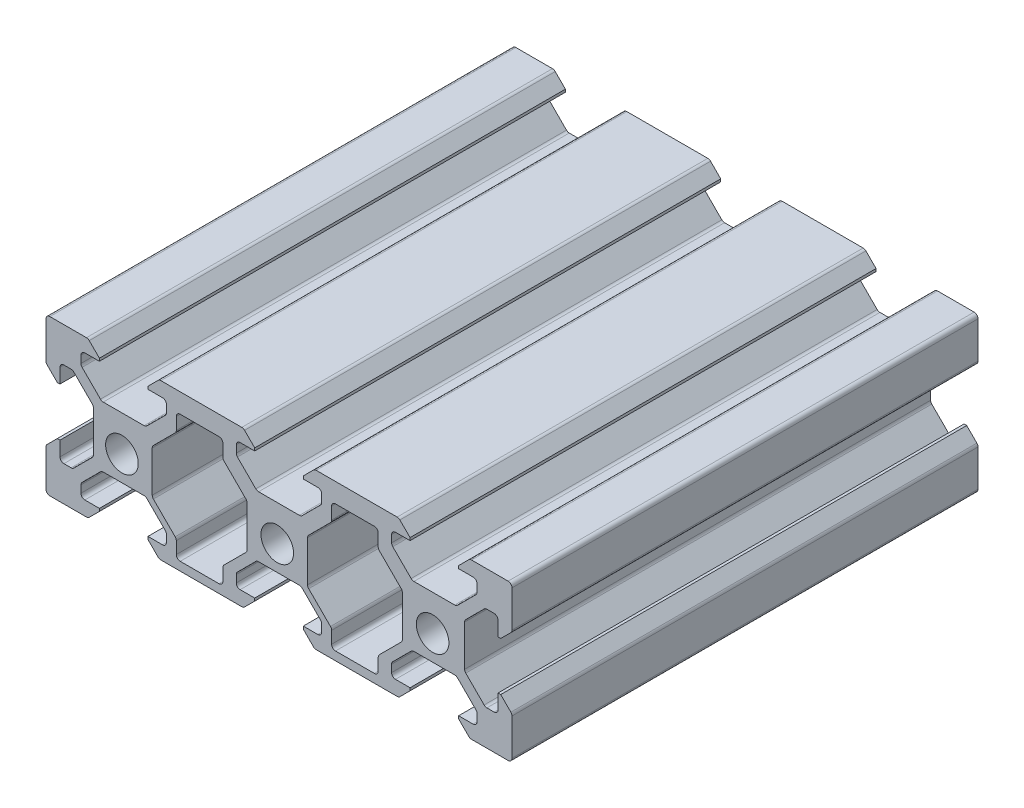
SolidWorks part; units mm, degrees
ref_plane "Front Plane" through (0, 0, 0) normal (0, 0, 1) x (1, 0, 0)
ref_plane "Top Plane" through (0, 0, 0) normal (0, 1, 0) x (1, 0, 0)
ref_plane "Right Plane" through (0, 0, 0) normal (1, 0, 0) x (0, 0, -1)
sketch "Sketch1" plane through (0, 0, 0) normal (0, 0, 1) x (1, 0, 0)
  line L24 (-13, 7.7) -> (-13, 6.1464)
  line L25 (-12.5, 8.2) -> (-7.5, 8.2)
  line L26 (-7, 6.1464) -> (-7, 7.7)
  line L27 (-6.8536, 5.7929) -> (-4.0464, 2.9858)
  line L28 (-3.9, 2.6322) -> (-3.9, -2.6322)
  line L29 (-15.9536, 2.9858) -> (-13.1464, 5.7929)
  line L30 (-16.1, -2.6322) -> (-16.1, 2.6322)
  line L31 (-13.1464, -5.7929) -> (-15.9536, -2.9858)
  line L32 (-13, -6.1464) -> (-13, -7.7)
  line L33 (-7.5, -8.2) -> (-12.5, -8.2)
  line L34 (-7, -7.7) -> (-7, -6.1464)
  line L35 (-4.0464, -2.9858) -> (-6.8536, -5.7929)
  line L36 (12.5, -8.2) -> (7.5, -8.2)
  line L37 (7, -6.1464) -> (7, -7.7)
  line L38 (6.8536, -5.7929) -> (4.0464, -2.9858)
  line L39 (3.9, -2.6322) -> (3.9, 2.6322)
  line L40 (4.0464, 2.9858) -> (6.8536, 5.7929)
  line L41 (7, 7.7) -> (7, 6.1464)
  line L42 (7.5, 8.2) -> (12.5, 8.2)
  line L43 (13, 6.1464) -> (13, 7.7)
  line L44 (13.1464, 5.7929) -> (15.9536, 2.9858)
  line L45 (16.1, 2.6322) -> (16.1, -2.6322)
  line L46 (15.9536, -2.9858) -> (13.1464, -5.7929)
  line L47 (13, -7.7) -> (13, -6.1464)
  line L200 (-22.4092, -3.2009) -> (-17.1447, -3.2009)
  line L201 (-16.7912, -3.3473) -> (-14.4234, -5.7151)
  line L202 (-14.277, -6.0686) -> (-14.277, -7.0009)
  line L203 (-14.777, -7.5009) -> (-16.652, -7.5009)
  line L204 (-16.652, -7.5009) -> (-16.652, -7.8459)
  line L205 (-16.652, -7.8459) -> (-15.3434, -9.1544)
  line L206 (-14.9898, -9.3009) -> (-4.5641, -9.3009)
  line L207 (-4.2105, -9.1544) -> (-2.902, -7.8459)
  line L208 (-2.902, -7.8459) -> (-2.902, -7.5009)
  line L209 (-2.902, -7.5009) -> (-4.777, -7.5009)
  line L210 (-5.277, -7.0009) -> (-5.277, -6.0686)
  line L211 (-5.1305, -5.7151) -> (-2.7627, -3.3473)
  line L212 (-2.4092, -3.2009) -> (2.8553, -3.2009)
  line L213 (3.2088, -3.3473) -> (5.5766, -5.7151)
  line L214 (5.723, -6.0686) -> (5.723, -7.0009)
  line L215 (5.223, -7.5009) -> (3.348, -7.5009)
  line L216 (3.348, -7.5009) -> (3.348, -7.8459)
  line L217 (3.348, -7.8459) -> (4.6566, -9.1544)
  line L218 (5.0102, -9.3009) -> (15.4359, -9.3009)
  line L219 (15.7895, -9.1544) -> (17.098, -7.8459)
  line L220 (17.098, -7.8459) -> (17.098, -7.5009)
  line L221 (17.098, -7.5009) -> (15.223, -7.5009)
  line L222 (14.723, -7.0009) -> (14.723, -6.0686)
  line L223 (14.8695, -5.7151) -> (17.2373, -3.3473)
  line L224 (17.5908, -3.2009) -> (22.8553, -3.2009)
  line L225 (23.2088, -3.3473) -> (25.5766, -5.7151)
  line L226 (25.723, -6.0686) -> (25.723, -7.0009)
  line L227 (25.223, -7.5009) -> (23.348, -7.5009)
  line L228 (23.348, -7.5009) -> (23.348, -7.8459)
  line L229 (23.348, -7.8459) -> (24.6566, -9.1544)
  line L230 (25.0102, -9.3009) -> (29.723, -9.3009)
  line L231 (30.223, -8.8009) -> (30.223, -4.088)
  line L232 (30.0766, -3.7344) -> (28.768, -2.4259)
  line L233 (28.768, -2.4259) -> (28.423, -2.4259)
  line L234 (28.423, -2.4259) -> (28.423, -4.3009)
  line L235 (27.923, -4.8009) -> (26.9908, -4.8009)
  line L236 (26.6373, -4.6544) -> (24.2695, -2.2866)
  line L237 (24.123, -1.9331) -> (24.123, 3.3314)
  line L238 (24.2695, 3.6849) -> (26.6373, 6.0527)
  line L239 (26.9908, 6.1991) -> (27.923, 6.1991)
  line L240 (28.423, 5.6991) -> (28.423, 3.8241)
  line L241 (28.423, 3.8241) -> (28.768, 3.8241)
  line L242 (28.768, 3.8241) -> (30.0766, 5.1327)
  line L243 (30.223, 5.4863) -> (30.223, 10.1991)
  line L244 (29.723, 10.6991) -> (25.0102, 10.6991)
  line L245 (24.6566, 10.5527) -> (23.348, 9.2441)
  line L246 (23.348, 9.2441) -> (23.348, 8.8991)
  line L247 (23.348, 8.8991) -> (25.223, 8.8991)
  line L248 (25.723, 8.3991) -> (25.723, 7.4669)
  line L249 (25.5766, 7.1134) -> (23.2088, 4.7456)
  line L250 (22.8553, 4.5991) -> (17.5908, 4.5991)
  line L251 (17.2373, 4.7456) -> (14.8695, 7.1134)
  line L252 (14.723, 7.4669) -> (14.723, 8.3991)
  line L253 (15.223, 8.8991) -> (17.098, 8.8991)
  line L254 (17.098, 8.8991) -> (17.098, 9.2441)
  line L255 (17.098, 9.2441) -> (15.7895, 10.5527)
  line L256 (15.4359, 10.6991) -> (5.0102, 10.6991)
  line L257 (4.6566, 10.5527) -> (3.348, 9.2441)
  line L258 (3.348, 9.2441) -> (3.348, 8.8991)
  line L259 (3.348, 8.8991) -> (5.223, 8.8991)
  line L260 (5.723, 8.3991) -> (5.723, 7.4669)
  line L261 (5.5766, 7.1134) -> (3.2088, 4.7456)
  line L262 (2.8553, 4.5991) -> (-2.4092, 4.5991)
  line L263 (-2.7627, 4.7456) -> (-5.1305, 7.1134)
  line L264 (-5.277, 7.4669) -> (-5.277, 8.3991)
  line L265 (-4.777, 8.8991) -> (-2.902, 8.8991)
  line L266 (-2.902, 8.8991) -> (-2.902, 9.2441)
  line L267 (-2.902, 9.2441) -> (-4.2105, 10.5527)
  line L268 (-4.5641, 10.6991) -> (-14.9898, 10.6991)
  line L269 (-15.3434, 10.5527) -> (-16.652, 9.2441)
  line L270 (-16.652, 9.2441) -> (-16.652, 8.8991)
  line L271 (-16.652, 8.8991) -> (-14.777, 8.8991)
  line L272 (-14.277, 8.3991) -> (-14.277, 7.4669)
  line L273 (-14.4234, 7.1134) -> (-16.7912, 4.7456)
  line L274 (-17.1447, 4.5991) -> (-22.4092, 4.5991)
  line L275 (-22.7627, 4.7456) -> (-25.1305, 7.1134)
  line L276 (-25.277, 7.4669) -> (-25.277, 8.3991)
  line L277 (-24.777, 8.8991) -> (-22.902, 8.8991)
  line L278 (-22.902, 8.8991) -> (-22.902, 9.2441)
  line L279 (-22.902, 9.2441) -> (-24.2105, 10.5527)
  line L280 (-24.5641, 10.6991) -> (-29.277, 10.6991)
  line L281 (-29.777, 10.1991) -> (-29.777, 5.4863)
  line L282 (-29.6305, 5.1327) -> (-28.322, 3.8241)
  line L283 (-28.322, 3.8241) -> (-27.977, 3.8241)
  line L284 (-27.977, 3.8241) -> (-27.977, 5.6991)
  line L285 (-27.477, 6.1991) -> (-26.5447, 6.1991)
  line L286 (-26.1912, 6.0527) -> (-23.8234, 3.6849)
  line L287 (-23.677, 3.3314) -> (-23.677, -1.9331)
  line L288 (-23.8234, -2.2866) -> (-26.1912, -4.6544)
  line L289 (-26.5447, -4.8009) -> (-27.477, -4.8009)
  line L290 (-27.977, -4.3009) -> (-27.977, -2.4259)
  line L291 (-27.977, -2.4259) -> (-28.322, -2.4259)
  line L292 (-28.322, -2.4259) -> (-29.6305, -3.7344)
  line L293 (-29.777, -4.088) -> (-29.777, -8.8009)
  line L294 (-29.277, -9.3009) -> (-24.5641, -9.3009)
  line L295 (-24.2105, -9.1544) -> (-22.902, -7.8459)
  line L296 (-22.902, -7.8459) -> (-22.902, -7.5009)
  line L297 (-22.902, -7.5009) -> (-24.777, -7.5009)
  line L298 (-25.277, -7.0009) -> (-25.277, -6.0686)
  line L299 (-25.1305, -5.7151) -> (-22.7627, -3.3473)
  arc A27 (-13.1464, 5.7929) -> (-13, 6.1464) centre (-13.5, 6.1464) ccw
  arc A28 (-12.5, 8.2) -> (-13, 7.7) centre (-12.5, 7.7) ccw
  arc A29 (-7, 7.7) -> (-7.5, 8.2) centre (-7.5, 7.7) ccw
  arc A30 (-7, 6.1464) -> (-6.8536, 5.7929) centre (-6.5, 6.1464) ccw
  arc A31 (-3.9, 2.6322) -> (-4.0464, 2.9858) centre (-4.4, 2.6322) ccw
  arc A32 (-15.9536, 2.9858) -> (-16.1, 2.6322) centre (-15.6, 2.6322) ccw
  circle A33 centre (-20, 0) radius 2.1
  arc A34 (-16.1, -2.6322) -> (-15.9536, -2.9858) centre (-15.6, -2.6322) ccw
  arc A35 (-13, -6.1464) -> (-13.1464, -5.7929) centre (-13.5, -6.1464) ccw
  arc A36 (-13, -7.7) -> (-12.5, -8.2) centre (-12.5, -7.7) ccw
  arc A37 (-7.5, -8.2) -> (-7, -7.7) centre (-7.5, -7.7) ccw
  arc A38 (-6.8536, -5.7929) -> (-7, -6.1464) centre (-6.5, -6.1464) ccw
  arc A39 (-4.0464, -2.9858) -> (-3.9, -2.6322) centre (-4.4, -2.6322) ccw
  circle A40 centre (0, 0) radius 2.1
  arc A41 (7, -7.7) -> (7.5, -8.2) centre (7.5, -7.7) ccw
  arc A42 (7, -6.1464) -> (6.8536, -5.7929) centre (6.5, -6.1464) ccw
  arc A43 (3.9, -2.6322) -> (4.0464, -2.9858) centre (4.4, -2.6322) ccw
  arc A44 (4.0464, 2.9858) -> (3.9, 2.6322) centre (4.4, 2.6322) ccw
  arc A45 (6.8536, 5.7929) -> (7, 6.1464) centre (6.5, 6.1464) ccw
  arc A46 (7.5, 8.2) -> (7, 7.7) centre (7.5, 7.7) ccw
  arc A47 (13, 7.7) -> (12.5, 8.2) centre (12.5, 7.7) ccw
  arc A48 (13, 6.1464) -> (13.1464, 5.7929) centre (13.5, 6.1464) ccw
  arc A49 (16.1, 2.6322) -> (15.9536, 2.9858) centre (15.6, 2.6322) ccw
  arc A50 (15.9536, -2.9858) -> (16.1, -2.6322) centre (15.6, -2.6322) ccw
  arc A51 (13.1464, -5.7929) -> (13, -6.1464) centre (13.5, -6.1464) ccw
  arc A52 (12.5, -8.2) -> (13, -7.7) centre (12.5, -7.7) ccw
  circle A53 centre (20, 0) radius 2.1
  arc A136 (-22.4092, -3.2009) -> (-22.7627, -3.3473) centre (-22.4092, -3.7009) ccw
  arc A137 (-16.7912, -3.3473) -> (-17.1447, -3.2009) centre (-17.1447, -3.7009) ccw
  arc A138 (-14.277, -6.0686) -> (-14.4234, -5.7151) centre (-14.777, -6.0686) ccw
  arc A139 (-14.777, -7.5009) -> (-14.277, -7.0009) centre (-14.777, -7.0009) ccw
  arc A140 (-15.3434, -9.1544) -> (-14.9898, -9.3009) centre (-14.9898, -8.8009) ccw
  arc A141 (-4.5641, -9.3009) -> (-4.2105, -9.1544) centre (-4.5641, -8.8009) ccw
  arc A142 (-5.277, -7.0009) -> (-4.777, -7.5009) centre (-4.777, -7.0009) ccw
  arc A143 (-5.1305, -5.7151) -> (-5.277, -6.0686) centre (-4.777, -6.0686) ccw
  arc A144 (-2.4092, -3.2009) -> (-2.7627, -3.3473) centre (-2.4092, -3.7009) ccw
  arc A145 (3.2088, -3.3473) -> (2.8553, -3.2009) centre (2.8553, -3.7009) ccw
  arc A146 (5.723, -6.0686) -> (5.5766, -5.7151) centre (5.223, -6.0686) ccw
  arc A147 (5.223, -7.5009) -> (5.723, -7.0009) centre (5.223, -7.0009) ccw
  arc A148 (4.6566, -9.1544) -> (5.0102, -9.3009) centre (5.0102, -8.8009) ccw
  arc A149 (15.4359, -9.3009) -> (15.7895, -9.1544) centre (15.4359, -8.8009) ccw
  arc A150 (14.723, -7.0009) -> (15.223, -7.5009) centre (15.223, -7.0009) ccw
  arc A151 (14.8695, -5.7151) -> (14.723, -6.0686) centre (15.223, -6.0686) ccw
  arc A152 (17.5908, -3.2009) -> (17.2373, -3.3473) centre (17.5908, -3.7009) ccw
  arc A153 (23.2088, -3.3473) -> (22.8553, -3.2009) centre (22.8553, -3.7009) ccw
  arc A154 (25.723, -6.0686) -> (25.5766, -5.7151) centre (25.223, -6.0686) ccw
  arc A155 (25.223, -7.5009) -> (25.723, -7.0009) centre (25.223, -7.0009) ccw
  arc A156 (24.6566, -9.1544) -> (25.0102, -9.3009) centre (25.0102, -8.8009) ccw
  arc A157 (29.723, -9.3009) -> (30.223, -8.8009) centre (29.723, -8.8009) ccw
  arc A158 (30.223, -4.088) -> (30.0766, -3.7344) centre (29.723, -4.088) ccw
  arc A159 (27.923, -4.8009) -> (28.423, -4.3009) centre (27.923, -4.3009) ccw
  arc A160 (26.6373, -4.6544) -> (26.9908, -4.8009) centre (26.9908, -4.3009) ccw
  arc A161 (24.123, -1.9331) -> (24.2695, -2.2866) centre (24.623, -1.9331) ccw
  arc A162 (24.2695, 3.6849) -> (24.123, 3.3314) centre (24.623, 3.3314) ccw
  arc A163 (26.9908, 6.1991) -> (26.6373, 6.0527) centre (26.9908, 5.6991) ccw
  arc A164 (28.423, 5.6991) -> (27.923, 6.1991) centre (27.923, 5.6991) ccw
  arc A165 (30.0766, 5.1327) -> (30.223, 5.4863) centre (29.723, 5.4863) ccw
  arc A166 (30.223, 10.1991) -> (29.723, 10.6991) centre (29.723, 10.1991) ccw
  arc A167 (25.0102, 10.6991) -> (24.6566, 10.5527) centre (25.0102, 10.1991) ccw
  arc A168 (25.723, 8.3991) -> (25.223, 8.8991) centre (25.223, 8.3991) ccw
  arc A169 (25.5766, 7.1134) -> (25.723, 7.4669) centre (25.223, 7.4669) ccw
  arc A170 (22.8553, 4.5991) -> (23.2088, 4.7456) centre (22.8553, 5.0991) ccw
  arc A171 (17.2373, 4.7456) -> (17.5908, 4.5991) centre (17.5908, 5.0991) ccw
  arc A172 (14.723, 7.4669) -> (14.8695, 7.1134) centre (15.223, 7.4669) ccw
  arc A173 (15.223, 8.8991) -> (14.723, 8.3991) centre (15.223, 8.3991) ccw
  arc A174 (15.7895, 10.5527) -> (15.4359, 10.6991) centre (15.4359, 10.1991) ccw
  arc A175 (5.0102, 10.6991) -> (4.6566, 10.5527) centre (5.0102, 10.1991) ccw
  arc A176 (5.723, 8.3991) -> (5.223, 8.8991) centre (5.223, 8.3991) ccw
  arc A177 (5.5766, 7.1134) -> (5.723, 7.4669) centre (5.223, 7.4669) ccw
  arc A178 (2.8553, 4.5991) -> (3.2088, 4.7456) centre (2.8553, 5.0991) ccw
  arc A179 (-2.7627, 4.7456) -> (-2.4092, 4.5991) centre (-2.4092, 5.0991) ccw
  arc A180 (-5.277, 7.4669) -> (-5.1305, 7.1134) centre (-4.777, 7.4669) ccw
  arc A181 (-4.777, 8.8991) -> (-5.277, 8.3991) centre (-4.777, 8.3991) ccw
  arc A182 (-4.2105, 10.5527) -> (-4.5641, 10.6991) centre (-4.5641, 10.1991) ccw
  arc A183 (-14.9898, 10.6991) -> (-15.3434, 10.5527) centre (-14.9898, 10.1991) ccw
  arc A184 (-14.277, 8.3991) -> (-14.777, 8.8991) centre (-14.777, 8.3991) ccw
  arc A185 (-14.4234, 7.1134) -> (-14.277, 7.4669) centre (-14.777, 7.4669) ccw
  arc A186 (-17.1447, 4.5991) -> (-16.7912, 4.7456) centre (-17.1447, 5.0991) ccw
  arc A187 (-22.7627, 4.7456) -> (-22.4092, 4.5991) centre (-22.4092, 5.0991) ccw
  arc A188 (-25.277, 7.4669) -> (-25.1305, 7.1134) centre (-24.777, 7.4669) ccw
  arc A189 (-24.777, 8.8991) -> (-25.277, 8.3991) centre (-24.777, 8.3991) ccw
  arc A190 (-24.2105, 10.5527) -> (-24.5641, 10.6991) centre (-24.5641, 10.1991) ccw
  arc A191 (-29.277, 10.6991) -> (-29.777, 10.1991) centre (-29.277, 10.1991) ccw
  arc A192 (-29.777, 5.4863) -> (-29.6305, 5.1327) centre (-29.277, 5.4863) ccw
  arc A193 (-27.477, 6.1991) -> (-27.977, 5.6991) centre (-27.477, 5.6991) ccw
  arc A194 (-26.1912, 6.0527) -> (-26.5447, 6.1991) centre (-26.5447, 5.6991) ccw
  arc A195 (-23.677, 3.3314) -> (-23.8234, 3.6849) centre (-24.177, 3.3314) ccw
  arc A196 (-23.8234, -2.2866) -> (-23.677, -1.9331) centre (-24.177, -1.9331) ccw
  arc A197 (-26.5447, -4.8009) -> (-26.1912, -4.6544) centre (-26.5447, -4.3009) ccw
  arc A198 (-27.977, -4.3009) -> (-27.477, -4.8009) centre (-27.477, -4.3009) ccw
  arc A199 (-29.6305, -3.7344) -> (-29.777, -4.088) centre (-29.277, -4.088) ccw
  arc A200 (-29.777, -8.8009) -> (-29.277, -9.3009) centre (-29.277, -8.8009) ccw
  arc A201 (-24.5641, -9.3009) -> (-24.2105, -9.1544) centre (-24.5641, -8.8009) ccw
  arc A202 (-25.277, -7.0009) -> (-24.777, -7.5009) centre (-24.777, -7.0009) ccw
  arc A203 (-25.1305, -5.7151) -> (-25.277, -6.0686) centre (-24.777, -6.0686) ccw
extrude "Boss-Extrude1" add sketch "Sketch1" along normal blind 60
